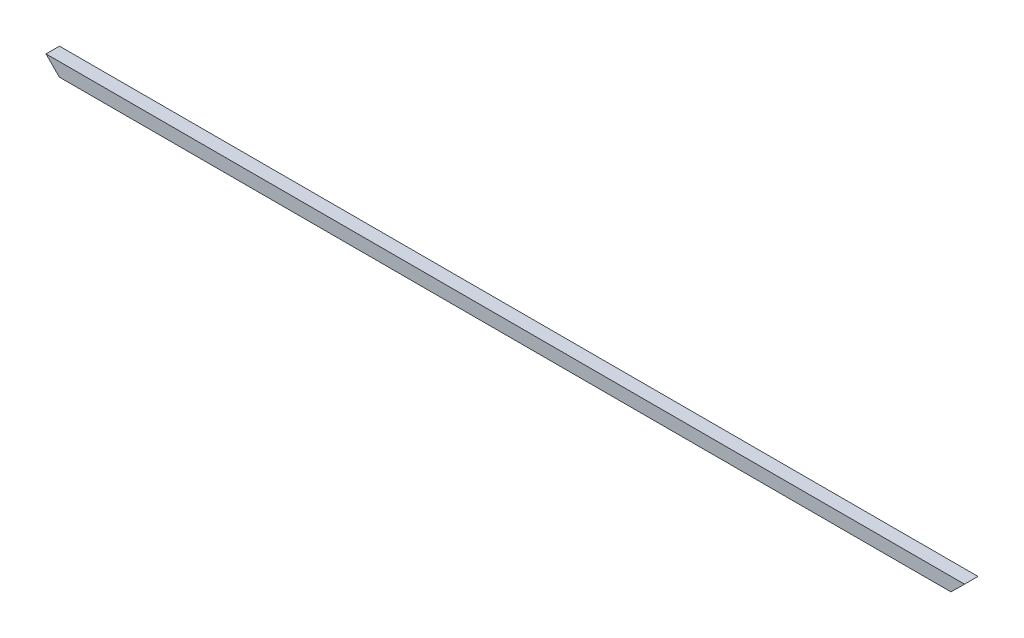
SolidWorks part; units mm, degrees
ref_plane "Front Plane" through (0, 0, 0) normal (0, 0, 1) x (1, 0, 0)
ref_plane "Top Plane" through (0, 0, 0) normal (0, 1, 0) x (1, 0, 0)
ref_plane "Right Plane" through (0, 0, 0) normal (1, 0, 0) x (0, 0, -1)
sketch "Sketch2" plane through (0, 0, 0) normal (0, 0, 1) x (1, 0, 0)
  line L0 (-2705.8207, 0) -> (23.6493, 0)
  line L1 (55, 0) -> (-55, 0) construction
  line L2 (23.6493, 0) -> (-16.7718, -40)
  line L3 (-16.7718, -40) -> (-2666.2374, -40)
  line L4 (-2666.2374, -40) -> (-2705.8207, 0)
  dimension "D1" = 45.3
  dimension "D2" = 44.7
  dimension "D3" = 2729.47
  dimension "D4" = 40
extrude "Boss-Extrude1" add sketch "Sketch2" along normal blind 40
